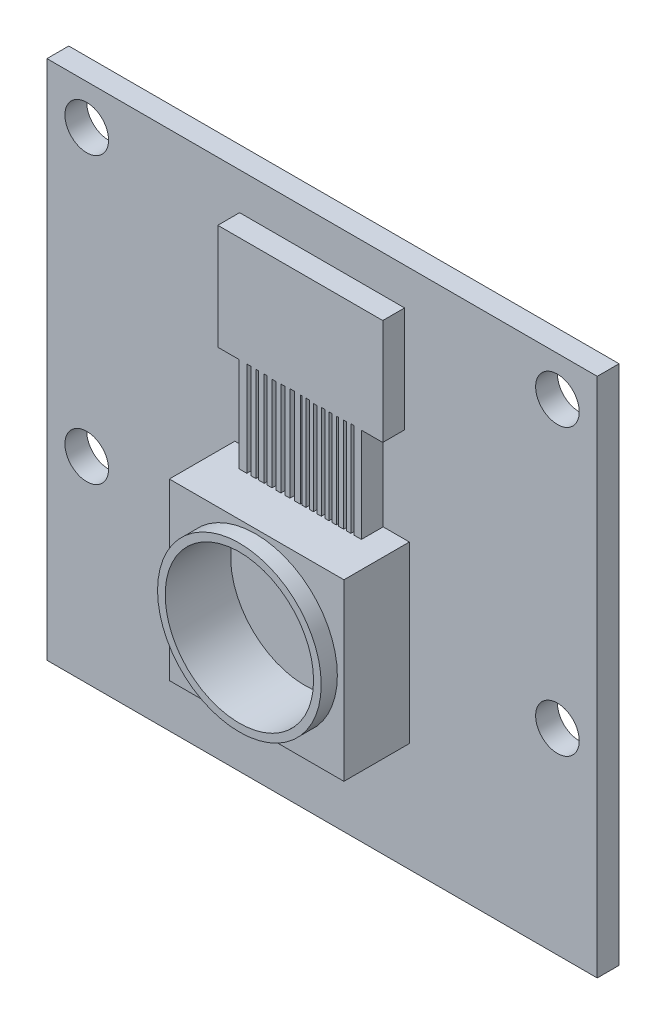
SolidWorks part; units mm, degrees
ref_plane "Front Plane" through (0, 0, 0) normal (0, 0, 1) x (1, 0, 0)
ref_plane "Top Plane" through (0, 0, 0) normal (0, 1, 0) x (1, 0, 0)
ref_plane "Right Plane" through (0, 0, 0) normal (1, 0, 0) x (0, 0, -1)
sketch "Sketch1" plane through (0, 0, 0) normal (0, 0, 1) x (1, 0, 0)
  line L0 (-47.4195, -18.5554) -> (-22.1995, -18.5554)
  line L1 (-22.1995, -18.5554) -> (-22.1995, 5.3246)
  line L2 (-22.1995, 5.3246) -> (-47.4195, 5.3246)
  line L3 (-47.4195, 5.3246) -> (-47.4195, -18.5554)
extrude "Boss-Extrude1" add sketch "Sketch1" along normal blind 1
sketch "Sketch2" plane through (0, 0, 1) normal (0, 0, 1) x (1, 0, 0)
  circle A0 centre (-24.0238, 3.5002) radius 1
  circle A1 centre (-45.5951, 3.5002) radius 1
extrude "Cut-Extrude1" cut sketch "Sketch2" against normal blind 15 and the other way blind 31
sketch "Sketch3" plane through (0, 0, 1) normal (0, 0, 1) x (1, 0, 0)
  line L2 (-34.8095, -13.5554) -> (-30.8095, -13.5554)
  line L3 (-34.8095, -13.5554) -> (-38.8095, -13.5554)
  line L4 (-38.8095, -13.5554) -> (-38.8095, -5.5554)
  line L5 (-38.8095, -5.5554) -> (-30.8095, -5.5554)
  line L6 (-30.8095, -5.5554) -> (-30.8095, -13.5554)
extrude "Boss-Extrude2" add sketch "Sketch3" along normal blind 3
sketch "Sketch5" plane through (0, 0, 4) normal (0, 0, 1) x (1, 0, 0)
  circle A0 centre (-34.8601, -9.5039) radius 3.75
extrude "Boss-Extrude4" add sketch "Sketch5" along normal blind 0.74
sketch "Sketch6" plane through (0, 0, 4.74) normal (0, 0, 1) x (1, 0, 0)
  circle A0 centre (-34.8601, -9.5039) radius 3.4
extrude "Cut-Extrude2" cut sketch "Sketch6" against normal blind 3
sketch "Sketch7" plane through (0, 0, 1) normal (0, 0, 1) x (1, 0, 0)
  line L2 (-30.8095, -5.5554) -> (-30.8095, -13.5554)
  circle A0 centre (-24.0238, -9.5554) radius 1
  circle A1 centre (-45.5951, -9.5554) radius 1
extrude "Cut-Extrude3" cut sketch "Sketch7" against normal blind 20 and the other way blind 16 contours A0 | A1
sketch "Sketch8" plane through (0, 0, 1) normal (0, 0, 1) x (1, 0, 0)
  line L0 (-38.5895, 3.6246) -> (-38.5895, -1.2154)
  line L2 (-34.8095, 3.6246) -> (-31.0295, 3.6246)
  line L3 (-34.8095, 3.6246) -> (-38.5895, 3.6246)
  line L4 (-32.0095, -1.2154) -> (-31.0295, -1.2154)
  line L7 (-38.5895, -1.2154) -> (-37.6095, -1.2154)
  line L8 (-37.6095, -1.2154) -> (-37.6095, -5.5554)
  line L9 (-30.8095, -5.5554) -> (-38.8095, -5.5554) construction
  line L10 (-37.6095, -5.5554) -> (-32.0095, -5.5554)
  line L11 (-32.0095, -5.5554) -> (-32.0095, -1.2154)
  line L12 (-31.0295, -1.2154) -> (-31.0295, 3.6246)
extrude "Boss-Extrude5" add sketch "Sketch8" along normal blind 1
sketch "Sketch9" plane through (0, 0, 1) normal (0, 0, 1) x (1, 0, 0)
  line L0 (-37.6095, -5.5554) -> (-36.9095, -5.5554)
  line L1 (-37.6095, -5.5554) -> (-32.0095, -5.5554) construction
  line L2 (-36.9095, -5.5554) -> (-36.2095, -5.5554)
  line L3 (-36.2095, -5.5554) -> (-35.5095, -5.5554)
  line L4 (-35.5095, -5.5554) -> (-34.8095, -5.5554)
  line L5 (-34.8095, -5.5554) -> (-34.1095, -5.5554)
  line L6 (-30.8095, -5.5554) -> (-38.8095, -5.5554) construction
  line L7 (-34.1095, -5.5554) -> (-33.4095, -5.5554)
  line L8 (-33.4095, -5.5554) -> (-32.7095, -5.5554)
  line L9 (-32.7095, -5.5554) -> (-32.0095, -5.5554)
  line L10 (-37.2595, -5.5554) -> (-37.2595, -1.2154)
  line L11 (-37.2595, -1.2154) -> (-37.0595, -1.2154)
  line L12 (-37.0595, -1.2154) -> (-37.0595, -5.5554)
  line L13 (-37.0595, -5.5554) -> (-37.2595, -5.5554)
extrude "Cut-Extrude8" cut sketch "Sketch9" along normal blind 1 contours L12 L11 L10 L0
sketch "Sketch10" plane through (0, 0, 2) normal (0, 0, 1) x (1, 0, 0)
  line L1 (-30.8095, -5.5554) -> (-38.8095, -5.5554) construction
  line L2 (-36.8375, -5.5554) -> (-36.8375, -1.2154)
  line L3 (-36.8375, -1.2154) -> (-36.7128, -1.2154)
  line L4 (-36.7128, -1.2154) -> (-36.7128, -5.5554)
  line L5 (-36.7128, -5.5554) -> (-36.8375, -5.5554)
extrude "Cut-Extrude14" cut sketch "Sketch10" against normal blind 1
sketch "Sketch13" plane through (0, 0, 2) normal (0, 0, 1) x (1, 0, 0)
  line L1 (-36.7128, -5.5554) -> (-32.0095, -5.5554) construction
  line L2 (-36.461, -5.5554) -> (-36.461, -1.2154)
  line L3 (-36.461, -1.2154) -> (-36.34, -1.2154)
  line L4 (-36.34, -1.2154) -> (-36.34, -5.5554)
  line L5 (-36.34, -5.5554) -> (-36.461, -5.5554)
extrude "Cut-Extrude15" cut sketch "Sketch13" against normal blind 1
sketch "Sketch14" plane through (0, 0, 1) normal (0, 0, 1) x (1, 0, 0)
  line L1 (-36.34, -5.5554) -> (-32.0095, -5.5554) construction
  line L2 (-36.1053, -5.5554) -> (-36.1053, -1.2436)
  line L3 (-36.1053, -1.2436) -> (-35.9103, -1.2436)
  line L4 (-35.9103, -1.2436) -> (-35.9103, -5.5554)
  line L5 (-35.9103, -5.5554) -> (-36.1053, -5.5554)
extrude "Cut-Extrude18" cut sketch "Sketch14" along normal blind 1
sketch "Sketch15" plane through (0, 0, 4) normal (0, 0, 1) x (1, 0, 0)
  line L1 (-35.9103, -5.5554) -> (-32.0095, -5.5554) construction
  line L2 (-35.698, -5.5554) -> (-35.698, -1.2288)
  line L3 (-35.698, -1.2288) -> (-35.5143, -1.2288)
  line L4 (-35.5143, -1.2288) -> (-35.5143, -5.5554)
  line L5 (-35.5143, -5.5554) -> (-35.698, -5.5554)
extrude "Cut-Extrude21" cut sketch "Sketch15" against normal blind 3
sketch "Sketch16" plane through (0, 0, 2) normal (0, 0, 1) x (1, 0, 0)
  line L1 (-30.8095, -5.5554) -> (-38.8095, -5.5554) construction
  line L2 (-35.2834, -5.5554) -> (-35.2834, -1.2086)
  line L3 (-35.2834, -1.2086) -> (-35.0656, -1.2086)
  line L4 (-35.0656, -1.2086) -> (-35.0656, -5.5554)
  line L5 (-35.5143, -5.5554) -> (-32.0095, -5.5554) construction
  line L6 (-35.0656, -5.5554) -> (-35.2834, -5.5554)
extrude "Cut-Extrude22" cut sketch "Sketch16" against normal up to vertex (1 mm away) up to point (-35.5143, -1.2288, 1)
sketch "Sketch17" plane through (0, 0, 4) normal (0, 0, 1) x (1, 0, 0)
  line L1 (-30.8095, -5.5554) -> (-38.8095, -5.5554) construction
  line L2 (-34.8095, -5.5554) -> (-34.8095, -1.2125)
  line L3 (-34.8095, -1.2125) -> (-34.7203, -1.2125)
  line L4 (-34.7203, -1.2125) -> (-34.7203, -5.5554)
  line L5 (-35.0656, -5.5554) -> (-32.0095, -5.5554) construction
  line L6 (-34.7203, -5.5554) -> (-34.8095, -5.5554)
extrude "Cut-Extrude23" cut sketch "Sketch17" against normal blind 3
sketch "Sketch18" plane through (0, 0, 4) normal (0, 0, 1) x (1, 0, 0)
  line L1 (-30.8095, -5.5554) -> (-38.8095, -5.5554) construction
  line L2 (-34.5483, -5.5554) -> (-34.5483, -1.2137)
  line L3 (-34.5483, -1.2137) -> (-34.3921, -1.2137)
  line L4 (-34.3921, -1.2137) -> (-34.3921, -5.5554)
  line L5 (-34.7203, -5.5554) -> (-32.0095, -5.5554) construction
  line L6 (-34.3921, -5.5554) -> (-34.5483, -5.5554)
extrude "Cut-Extrude24" cut sketch "Sketch18" against normal blind 3
sketch "Sketch19" plane through (0, 0, 1) normal (0, 0, 1) x (1, 0, 0)
  line L2 (-34.3921, -5.5554) -> (-32.0095, -5.5554) construction
  line L3 (-34.2083, -5.5554) -> (-34.2083, -1.2546)
  line L4 (-34.2083, -1.2546) -> (-34.0364, -1.2546)
  line L5 (-34.0364, -1.2546) -> (-34.0364, -5.5554)
  line L6 (-34.0364, -5.5554) -> (-34.2083, -5.5554)
extrude "Cut-Extrude26" cut sketch "Sketch19" along normal blind 3
sketch "Sketch20" plane through (0, 0, 1) normal (0, 0, 1) x (1, 0, 0)
  line L1 (-34.0364, -5.5554) -> (-32.0095, -5.5554) construction
  line L2 (-33.8472, -5.5554) -> (-33.8472, -1.2281)
  line L3 (-33.8472, -1.2281) -> (-33.6763, -1.2281)
  line L4 (-33.6763, -1.2281) -> (-33.6763, -5.5554)
  line L5 (-33.6763, -5.5554) -> (-33.8472, -5.5554)
extrude "Cut-Extrude28" cut sketch "Sketch20" along normal blind 3
sketch "Sketch21" plane through (0, 0, 4) normal (0, 0, 1) x (1, 0, 0)
  line L1 (-33.6763, -5.5554) -> (-32.0095, -5.5554) construction
  line L2 (-33.4962, -5.5554) -> (-33.4962, -1.2337)
  line L3 (-33.4962, -1.2337) -> (-33.3587, -1.2337)
  line L4 (-33.3587, -1.2337) -> (-33.3587, -5.5554)
  line L5 (-33.3587, -5.5554) -> (-33.4962, -5.5554)
extrude "Cut-Extrude29" cut sketch "Sketch21" against normal blind 3
sketch "Sketch22" plane through (0, 0, 4) normal (0, 0, 1) x (1, 0, 0)
  line L1 (-33.3587, -5.5554) -> (-32.0095, -5.5554) construction
  line L2 (-33.1587, -5.5554) -> (-33.1587, -1.2309)
  line L3 (-33.1587, -1.2309) -> (-33.0577, -1.2309)
  line L4 (-33.0577, -1.2309) -> (-33.0577, -5.5554)
  line L5 (-33.0577, -5.5554) -> (-33.1587, -5.5554)
extrude "Cut-Extrude30" cut sketch "Sketch22" against normal blind 3
sketch "Sketch23" plane through (0, 0, 4) normal (0, 0, 1) x (1, 0, 0)
  line L1 (-30.8095, -5.5554) -> (-38.8095, -5.5554) construction
  line L2 (-32.8236, -5.5554) -> (-32.8236, -1.2244)
  line L3 (-32.8236, -1.2244) -> (-32.6998, -1.2244)
  line L4 (-32.6998, -1.2244) -> (-32.6998, -5.5554)
  line L5 (-32.6998, -5.5554) -> (-32.8236, -5.5554)
extrude "Cut-Extrude31" cut sketch "Sketch23" against normal blind 3
sketch "Sketch24" plane through (0, 0, 4) normal (0, 0, 1) x (1, 0, 0)
  line L1 (-32.6998, -5.5554) -> (-32.0095, -5.5554) construction
  line L2 (-32.4881, -5.5554) -> (-32.4881, -1.2006)
  line L3 (-32.4881, -1.2006) -> (-32.3546, -1.2006)
  line L4 (-32.3546, -1.2006) -> (-32.3546, -5.5554)
  line L5 (-32.3546, -5.5554) -> (-32.4881, -5.5554)
extrude "Cut-Extrude32" cut sketch "Sketch24" against normal blind 3
